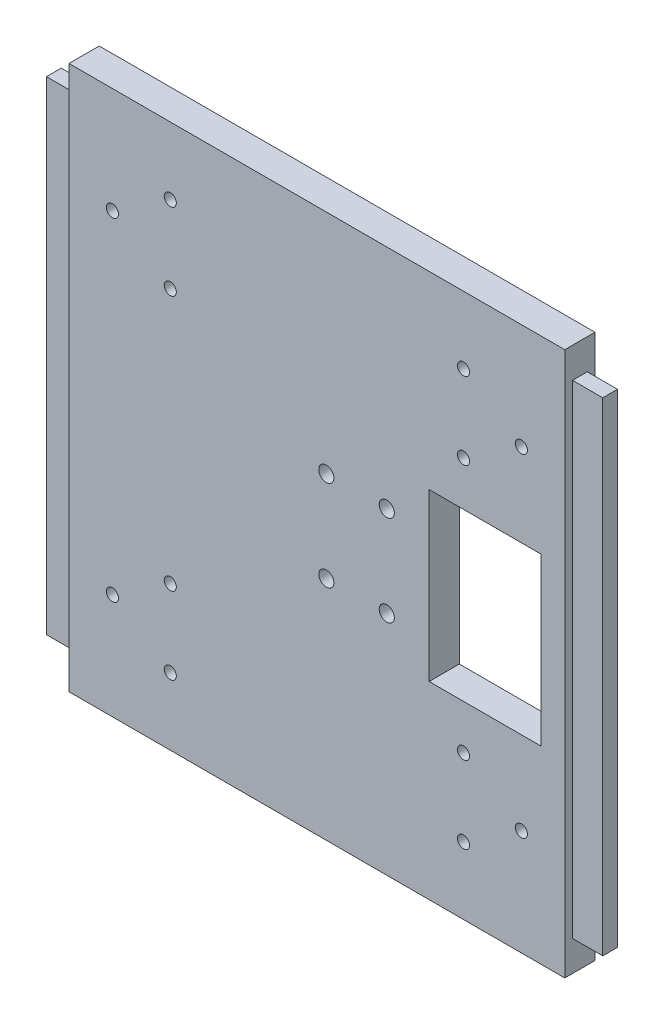
SolidWorks part; units mm, degrees
ref_plane "前视基准面" through (0, 0, 0) normal (0, 0, 1) x (1, 0, 0)
ref_plane "上视基准面" through (0, 0, 0) normal (0, 1, 0) x (1, 0, 0)
ref_plane "右视基准面" through (0, 0, 0) normal (1, 0, 0) x (0, 0, -1)
other "Configuration Table"
sketch "草图1" plane through (0, 0, 0) normal (0, 0, 1) x (1, 0, 0)
  line L1 (0, 0) -> (164, 0)
  line L2 (0, 0) -> (0, 180)
  line L3 (0, 180) -> (164, 180)
  line L4 (164, 0) -> (164, 180)
  line L5 (0, 0) -> (164, 180) construction
  line L6 (0, 180) -> (164, 0) construction
  point P4 (82, 90)
  dimension "D1" = 164
  dimension "D2" = 180
extrude "凸台-拉伸1" add sketch "草图1" along normal blind 10
sketch "草图2" plane through (0, 0, 0) normal (-1, 0, 0) x (0, 0, 1)
  line L0 (10, 180) -> (10, 0) construction
  line L1 (2.56, 169.94) -> (7.44, 169.94)
  line L2 (2.56, 169.94) -> (2.56, 10.06)
  line L3 (2.56, 10.06) -> (7.44, 10.06)
  line L4 (7.44, 169.94) -> (7.44, 10.06)
  line L5 (2.56, 169.94) -> (7.44, 10.06) construction
  line L6 (2.56, 10.06) -> (7.44, 169.94) construction
  line L7 (10, 180) -> (0, 180) construction
  point P4 (5, 90)
  dimension "D1" = 4.88
  dimension "D2" = 159.88
  dimension "D3" = 5
  dimension "D4" = 90
extrude "凸台-拉伸2" add sketch "草图2" along normal blind 10
ref_plane "基准面1" through (82, 0, 0) normal (1, 0, 0) x (0, 0, -1)
mirror "镜向1" about plane through (82, 0, 0) normal (1, 0, 0) of "凸台-拉伸2"
sketch "草图3" plane through (0, 0, 0) normal (0, 0, -1) x (-1, 0, 0)
  line L0 (-164, 169.94) -> (-164, 10.06) construction
  line L1 (-164, 90) -> (12.5762, 90) construction
  line L2 (-174, 169.94) -> (-174, 10.06) construction
  line L3 (-164, 0) -> (-164, 180) construction
  line L4 (0, 169.94) -> (0, 10.06) construction
  line L5 (0, 180) -> (0, 0) construction
  circle A0 centre (-149.6426, 145) radius 2
  circle A1 centre (-130.5, 157.75) radius 2
  circle A2 centre (-130.5, 132.25) radius 2
  circle A3 centre (-14.3574, 145) radius 2
  circle A4 centre (-33.5, 157.75) radius 2
  circle A5 centre (-33.5, 132.25) radius 2
  circle A6 centre (-130.5, 47.75) radius 2
  circle A7 centre (-130.5, 22.25) radius 2
  circle A8 centre (-149.6426, 35) radius 2
  circle A9 centre (-33.5, 47.75) radius 2
  circle A10 centre (-33.5, 22.25) radius 2
  circle A11 centre (-14.3574, 35) radius 2
  dimension "D1" = 4
  dimension "D2" = 4
  dimension "D3" = 4
  dimension "D4" = 4
  dimension "D5" = 4
  dimension "D6" = 4
  dimension "D7" = 23
  dimension "D8" = 23
  dimension "D9" = 25.5
  dimension "D10" = 10
  dimension "D11" = 55
  dimension "D12" = 33.5
  dimension "D13" = 25.5
  dimension "D14" = 23
  dimension "D15" = 23
  dimension "D16" = 33.5
  dimension "D17" = 33.5
  dimension "D18" = 55
  dimension "D19" = 33.5
extrude "切除-拉伸1" cut sketch "草图3" against normal blind 10
sketch "草图5" plane through (0, 0, 10) normal (0, 0, 1) x (1, 0, 0)
  line L0 (0, 90) -> (164, 90) construction
  line L1 (85.1179, 105) -> (85.1179, 75) construction
  line L3 (0, 10.06) -> (0, 169.94) construction
  line L4 (5, 110.5) -> (125, 110.5) construction
  line L5 (5, 110.5) -> (5, 69.5) construction
  line L6 (5, 69.5) -> (125, 69.5) construction
  line L7 (125, 110.5) -> (125, 69.5) construction
  line L8 (5, 110.5) -> (125, 69.5) construction
  line L9 (5, 69.5) -> (125, 110.5) construction
  line L10 (119.1179, 117.5) -> (156.1179, 117.5)
  line L11 (75.1179, 110) -> (118.1179, 110) construction
  line L12 (75.1179, 110) -> (75.1179, 70) construction
  line L13 (75.1179, 70) -> (118.1179, 70) construction
  line L14 (118.1179, 110) -> (118.1179, 70) construction
  line L15 (75.1179, 110) -> (118.1179, 70) construction
  line L16 (75.1179, 70) -> (118.1179, 110) construction
  line L17 (119.1179, 117.5) -> (119.1179, 62.5)
  line L18 (119.1179, 62.5) -> (156.1179, 62.5)
  line L19 (156.1179, 117.5) -> (156.1179, 62.5)
  line L20 (119.1179, 117.5) -> (156.1179, 62.5) construction
  line L21 (119.1179, 62.5) -> (156.1179, 117.5) construction
  circle A1 centre (85.1179, 105) radius 2.5
  circle A2 centre (85.1179, 75) radius 2.5
  circle A5 centre (105.1179, 105) radius 2.5
  circle A6 centre (105.1179, 75) radius 2.5
  point P5 (65, 90)
  point P13 (96.6179, 90)
  point P22 (85.1179, 90)
  point P27 (137.6179, 90)
  dimension "D5" = 43
  dimension "D7" = 5
  dimension "D8" = 2
  dimension "D9" = 5
  dimension "D10" = 55
  dimension "D1" = 120
  dimension "D2" = 41
  dimension "D3" = 5
  dimension "D4" = 6.8821
  dimension "D6" = 40
  dimension "D11" = 30
  dimension "D12" = 10
  dimension "D13" = 37
  dimension "D14" = 2
extrude "切除-拉伸3" cut sketch "草图5" against normal blind 8
sketch "草图6" plane through (0, 0, 2) normal (0, 0, 1) x (1, 0, 0)
  line L4 (119.1179, 117.5) -> (119.1179, 62.5)
  line L5 (119.1179, 62.5) -> (156.1179, 62.5)
  line L6 (156.1179, 62.5) -> (156.1179, 117.5)
  line L7 (156.1179, 117.5) -> (119.1179, 117.5)
  line L8 (119.1179, 117.5) -> (119.1179, 62.5)
  line L9 (119.1179, 62.5) -> (156.1179, 62.5)
  line L10 (156.1179, 62.5) -> (156.1179, 117.5)
  line L11 (156.1179, 117.5) -> (119.1179, 117.5)
  dimension "D1" = 0
extrude "切除-拉伸4" cut sketch "草图6" against normal blind 8
